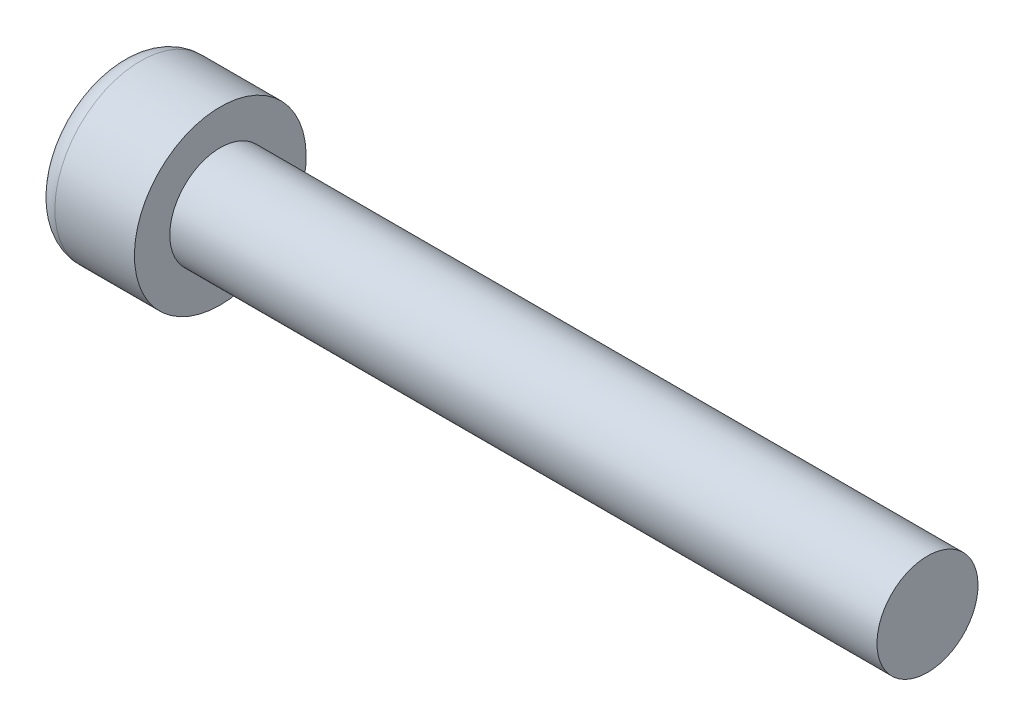
SolidWorks part; units mm, degrees
material "Plain Carbon Steel"
ref_plane "Front Plane" through (0, 0, 0) normal (0, 0, 1) x (1, 0, 0)
ref_plane "Top Plane" through (0, 0, 0) normal (0, 1, 0) x (1, 0, 0)
ref_plane "Right Plane" through (0, 0, 0) normal (1, 0, 0) x (0, 0, -1)
sketch "Sketch1" plane through (0, 0, 0) normal (0, 0, 1) x (1, 0, 0)
  line L0 (0, 0) -> (0, 3.1875)
  line L1 (1.0625, 4.25) -> (5, 4.25)
  line L2 (5, 4.25) -> (5, 2.5)
  line L3 (5, 2.5) -> (40, 2.5)
  line L4 (40, 2.5) -> (40, 0)
  line L5 (40, 0) -> (0, 0) construction
  line L6 (1.0625, 3.1875) -> (1.0625, 2.125) construction
  line L7 (1.0625, 2.125) -> (1.0625, 1.0625) construction
  line L8 (1.0625, 1.0625) -> (1.0625, 0) construction
  line L9 (1.0625, 4.25) -> (1.0625, 3.1875) construction
  line L10 (0, 0) -> (40, 0)
  arc A0 (0, 3.1875) -> (1.0625, 4.25) centre (1.0625, 3.1875) cw
  dimension "D1" = 5
  dimension "D2" = 8.5
  dimension "D3" = 5
  dimension "D4" = 35
revolve "Revolve1" add sketch "Sketch1" angle 360 about L10
sketch "Sketch2" plane through (0, 0, 0) normal (-1, 0, 0) x (0, 0, 1)
  line L1 (0, 2.3094) -> (-2, 1.1547)
  line L2 (-2, 1.1547) -> (-2, -1.1547)
  line L3 (-2, -1.1547) -> (0, -2.3094)
  line L4 (0, -2.3094) -> (2, -1.1547)
  line L5 (2, -1.1547) -> (2, 1.1547)
  line L6 (2, 1.1547) -> (0, 2.3094)
  circle A0 centre (0, 0) radius 2 construction
  dimension "D1" = 4
extrude "Cut-Extrude1" cut sketch "Sketch2" against normal blind 2.5
